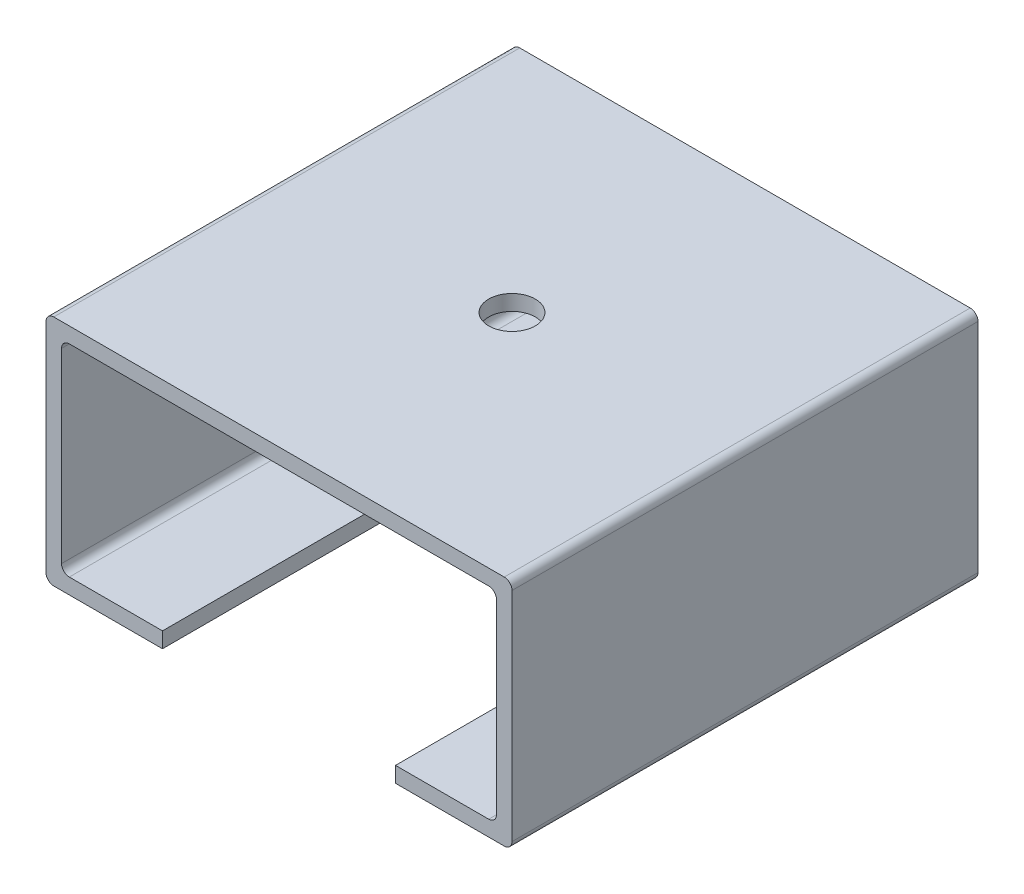
SolidWorks part; units mm, degrees
ref_plane "Front Plane" through (0, 0, 0) normal (0, 0, 1) x (1, 0, 0)
ref_plane "Top Plane" through (0, 0, 0) normal (0, 1, 0) x (1, 0, 0)
ref_plane "Right Plane" through (0, 0, 0) normal (1, 0, 0) x (0, 0, -1)
sketch "Sketch1" plane through (0, 0, 0) normal (0, 0, 1) x (1, 0, 0)
  line L0 (-15, 0) -> (-15, 2)
  line L1 (15, 0) -> (30, 0)
  line L2 (30, 0) -> (30, 30)
  line L3 (30, 30) -> (-30, 30)
  line L4 (-30, 30) -> (-30, 0)
  line L5 (-30, 0) -> (-15, 0)
  line L6 (-15, 2) -> (-28, 2)
  line L7 (-28, 2) -> (-28, 28)
  line L8 (15, 0) -> (15, 2)
  line L9 (15, 2) -> (28, 2)
  line L10 (28, 2) -> (28, 28)
  line L11 (28, 28) -> (-28, 28)
extrude "Boss-Extrude1" add sketch "Sketch1" along normal blind 60
fillet "Fillet1" radius 1 8 edges at (-30, 0, 30) (30, 0, 30) (30, 30, 30) (-30, 30, 30) (28, 2, 30) (28, 28, 30) (-28, 28, 30) (-28, 2, 30)
sketch "Sketch2" plane through (0, 30, 0) normal (0, 1, 0) x (1, 0, 0)
  circle A0 centre (0, -30) radius 3
extrude "Cut-Extrude1" cut sketch "Sketch2" against normal blind 2
